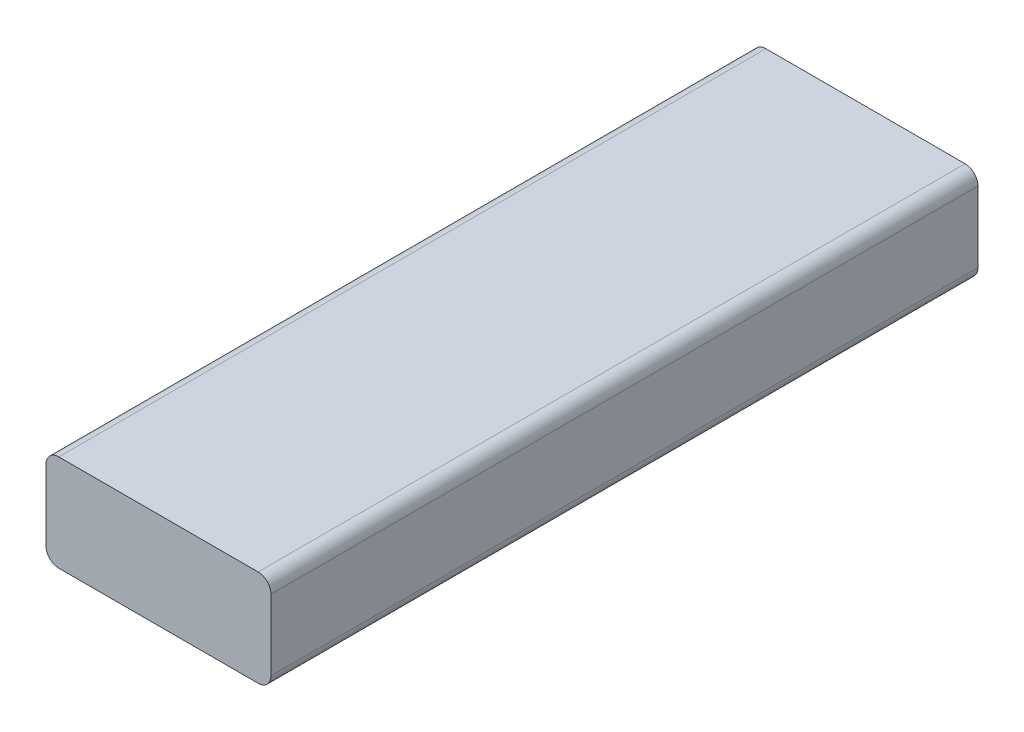
SolidWorks part; units mm, degrees
material "Oak"
ref_plane "Front Plane" through (0, 0, 0) normal (0, 0, 1) x (1, 0, 0)
ref_plane "Top Plane" through (0, 0, 0) normal (0, 1, 0) x (1, 0, 0)
ref_plane "Right Plane" through (0, 0, 0) normal (1, 0, 0) x (0, 0, -1)
sketch "Sketch1" plane through (0, 0, 0) normal (0, 0, 1) x (1, 0, 0)
  line L1 (0, 0) -> (88.9, 0)
  line L2 (0, 0) -> (0, 38.1)
  line L3 (0, 38.1) -> (88.9, 38.1)
  line L4 (88.9, 0) -> (88.9, 38.1)
  dimension "D1" = 38.1
  dimension "D2" = 88.9
extrude "Boss-Extrude1" add sketch "Sketch1" along normal blind 279.4
fillet "Fillet1" radius 5.08 4 edges at (88.9, 0, 139.7) (0, 0, 139.7) (0, 38.1, 139.7) (88.9, 38.1, 139.7)
